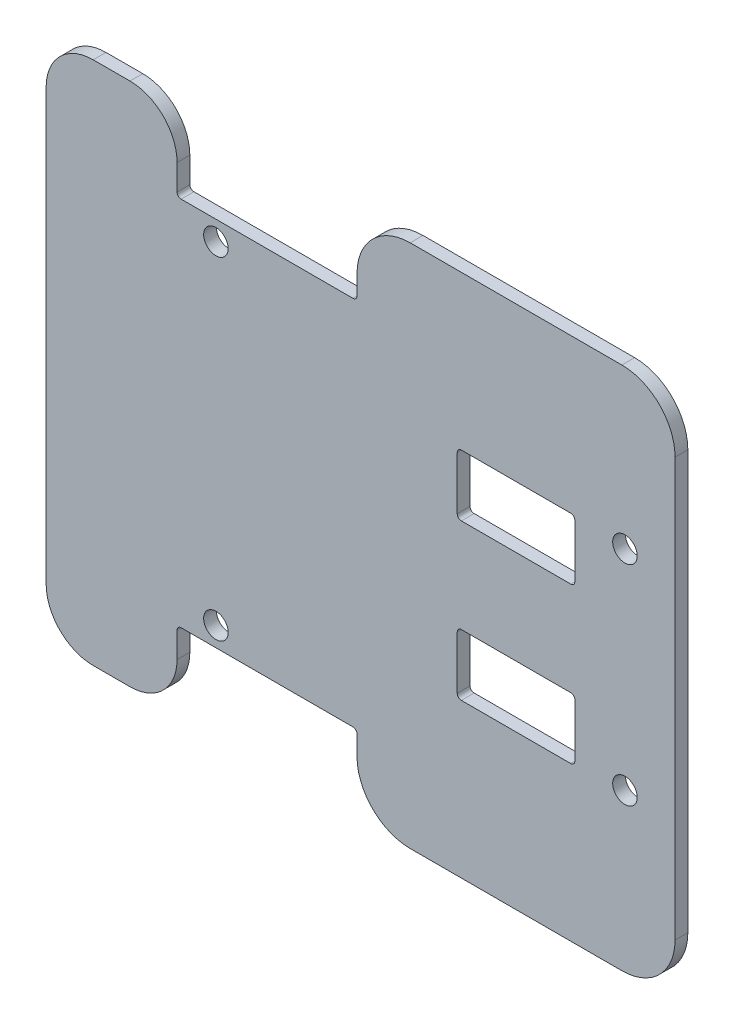
SolidWorks part; units mm, degrees
material "A-Glass Fiber"
ref_plane "Front Plane" through (0, 0, 0) normal (0, 0, 1) x (1, 0, 0)
ref_plane "Top Plane" through (0, 0, 0) normal (0, 1, 0) x (1, 0, 0)
ref_plane "Right Plane" through (0, 0, 0) normal (1, 0, 0) x (0, 0, -1)
sketch "Sketch1" plane through (0, 0, 0) normal (0, 0, 1) x (1, 0, 0)
  line L0 (33.274, 4.7625) -> (46.355, 4.7625)
  line L1 (46.355, -4.7625) -> (33.274, -4.7625)
  line L2 (-19.304, -25.8254) -> (-9.779, -25.8254)
  line L3 (-9.779, -25.8254) -> (-9.779, -31.3246)
  line L4 (-9.779, -31.3246) -> (-17.447, -31.3246)
  line L5 (-12.7, -33.3375) -> (-8.128, -33.3375)
  line L6 (-1.524, -26.7335) -> (-1.524, -15.5892)
  line L7 (-1.016, -15.0812) -> (18.796, -15.0812)
  line L8 (19.304, -15.5892) -> (19.304, -26.7335)
  line L9 (60.325, -26.7335) -> (60.325, 26.7335)
  line L10 (19.304, 26.7335) -> (19.304, 15.5892)
  line L11 (18.796, 15.0812) -> (-1.016, 15.0812)
  line L12 (-1.524, 15.5892) -> (-1.524, 26.7335)
  line L13 (-8.128, 33.3375) -> (-12.7, 33.3375)
  line L14 (-17.447, 31.3246) -> (-9.779, 31.3246)
  line L15 (-9.779, 31.3246) -> (-9.779, 25.8254)
  line L16 (-9.779, 25.8254) -> (-19.304, 25.8254)
  line L17 (-19.304, 25.8254) -> (-19.304, -25.8254)
  arc A0 (-17.447, -31.3246) -> (-12.7, -33.3375) centre (-12.7, -26.7335) ccw
  arc A1 (-8.128, -33.3375) -> (-1.524, -26.7335) centre (-8.128, -26.7335) ccw
  arc A2 (-1.016, -15.0812) -> (-1.524, -15.5892) centre (-1.016, -15.5892) ccw
  arc A3 (19.304, -15.5892) -> (18.796, -15.0812) centre (18.796, -15.5892) ccw
  arc A4 (18.796, 15.0812) -> (19.304, 15.5892) centre (18.796, 15.5892) ccw
  arc A5 (-1.524, 15.5892) -> (-1.016, 15.0812) centre (-1.016, 15.5892) ccw
  arc A6 (-1.524, 26.7335) -> (-8.128, 33.3375) centre (-8.128, 26.7335) ccw
  arc A7 (-12.7, 33.3375) -> (-17.447, 31.3246) centre (-12.7, 26.7335) ccw
  point P22 (0, 0)
sketch "Sketch2" plane through (0, 0, 0) normal (0, 0, 1) x (1, 0, 0)
  line L0 (32.512, 13.462) -> (18.796, 13.462) construction
  line L1 (18.796, 13.462) -> (18.796, 23.0505) construction
  line L2 (-2.286, 26.7335) -> (-2.286, 23.0505)
  line L3 (-8.128, 32.5755) -> (-12.7, 32.5755)
  line L4 (-18.542, 26.7335) -> (-18.542, -26.7335)
  line L5 (32.512, -5.842) -> (32.512, -13.462)
  line L6 (47.117, -13.462) -> (47.117, -5.842)
  line L7 (59.563, -13.462) -> (47.117, -13.462) construction
  line L8 (32.512, -5.842) -> (47.117, -5.842)
  line L9 (18.796, -23.0505) -> (-2.286, -23.0505)
  line L10 (-8.128, -32.5755) -> (-12.7, -32.5755)
  line L11 (-2.286, -26.7335) -> (-2.286, -23.0505)
  line L12 (18.796, -13.462) -> (18.796, -23.0505) construction
  line L13 (32.512, -13.462) -> (18.796, -13.462) construction
  line L14 (18.796, 23.0505) -> (20.066, 23.0505)
  line L15 (20.066, 23.0505) -> (20.066, 32.5755)
  line L16 (20.066, 32.5755) -> (59.563, 32.5755)
  line L17 (59.563, 32.5755) -> (59.563, 13.462)
  line L18 (19.304, 26.7335) -> (19.304, 15.5892) construction
  line L19 (18.796, -23.0505) -> (20.066, -23.0505)
  line L20 (59.563, -32.5755) -> (59.563, -13.462)
  line L21 (20.066, -32.5755) -> (59.563, -32.5755)
  line L22 (20.066, -23.0505) -> (20.066, -32.5755)
  line L23 (32.512, 13.462) -> (47.117, 13.462)
  line L24 (32.512, -13.462) -> (47.117, -13.462)
  line L71 (18.796, 23.0505) -> (-2.286, 23.0505)
  line L73 (59.563, -26.7335) -> (59.563, 26.7335)
  line L74 (59.563, -13.462) -> (59.563, 13.462)
  line L75 (0, 0) -> (-50000, 0) construction
  line L77 (32.512, 5.842) -> (47.117, 5.842)
  line L78 (59.563, 13.462) -> (47.117, 13.462) construction
  line L79 (47.117, 13.462) -> (47.117, 5.842)
  line L80 (33.274, 4.7625) -> (46.355, 4.7625) construction
  line L81 (32.512, 5.842) -> (32.512, 13.462)
  arc A0 (-12.7, -32.5755) -> (-18.542, -26.7335) centre (-12.7, -26.7335) cw
  arc A1 (-2.286, -26.7335) -> (-8.128, -32.5755) centre (-8.128, -26.7335) cw
  arc A38 (-2.286, 26.7335) -> (-8.128, 32.5755) centre (-8.128, 26.7335) ccw
  arc A39 (-2.286, 26.7335) -> (-8.128, 32.5755) centre (-8.128, 26.7335) ccw
  arc A41 (-12.7, 32.5755) -> (-16.8993, 30.7949) centre (-12.7, 26.7335) ccw
  arc A42 (-12.7, 32.5755) -> (-18.542, 26.7335) centre (-12.7, 26.7335) ccw
  point P36 (59.563, 0)
  point P38 (-18.542, 0)
  dimension "D6" = 0.762
  dimension "D7" = 8.6995
  dimension "D8" = 0.762
  dimension "D9" = 0.762
  dimension "D5" = 11.684
  dimension "D1" = 46.101
  dimension "D2" = 0.762
  dimension "D3" = 0.762
  dimension "D4" = 0.762
extrude "Boss-Extrude1" add sketch "Sketch2" along normal blind 1.5875
sketch "Sketch3" plane through (0, 0, 0) normal (0, 0, -1) x (-1, 0, 0)
  line L0 (0, 0) -> (50000, 0) construction
  line L1 (10.414, 32.5755) -> (10.414, 50032.5755) construction
  line L2 (8.128, 32.5755) -> (12.7, 32.5755) construction
  line L3 (-53.34, 11.938) -> (-53.34, 50011.938) construction
  line L5 (1.524, 5.6547) -> (1.524, 50005.6547) construction
  line L6 (2.286, 23.0505) -> (2.286, 26.7335) construction
  line L7 (-18.796, 23.0505) -> (1.524, 23.0505) construction
  line L8 (-20.066, 23.0505) -> (2.286, 23.0505) construction
  circle A0 centre (10.414, 22.225) radius 1.524 construction
  circle A1 centre (10.414, -22.225) radius 1.524 construction
  circle A2 centre (-53.34, 12.9857) radius 1.524
  circle A3 centre (-53.34, -12.9857) radius 1.524
  circle A4 centre (0, 0) radius 1.524 construction
  circle A5 centre (-2.54, 20.6375) radius 1.524
  circle A6 centre (-2.54, -20.6375) radius 1.524
  point P9 (10.414, 32.5755)
  dimension "D1" = 44.45
  dimension "D2" = 3.048
  dimension "D3" = 25.9715
  dimension "D4" = 41.275
  dimension "D5" = 0.762
  dimension "D6" = 53.34
  dimension "D7" = 50.8
extrude "Cut-Extrude1" cut sketch "Sketch3" against normal through all
fillet "Fillet1" radius 0.508 12 edges at (-2.286, -23.0505, 0.7937) (-2.286, 23.0505, 0.7937) (32.512, -5.842, 0.7937) (32.512, 5.842, 0.7937) (47.117, -5.842, 0.7937) (47.117, 5.842, 0.7937) (47.117, -13.462, 0.7937) (20.066, -23.0505, 0.7937) (32.512, -13.462, 0.7937) (32.512, 13.462, 0.7937) (47.117, 13.462, 0.7937) (20.066, 23.0505, 0.7937)
fillet "Fillet2" radius 6.604 4 edges at (59.563, 32.5755, 0.7937) (20.066, 32.5755, 0.7937) (59.563, -32.5755, 0.7937) (20.066, -32.5755, 0.7937)
